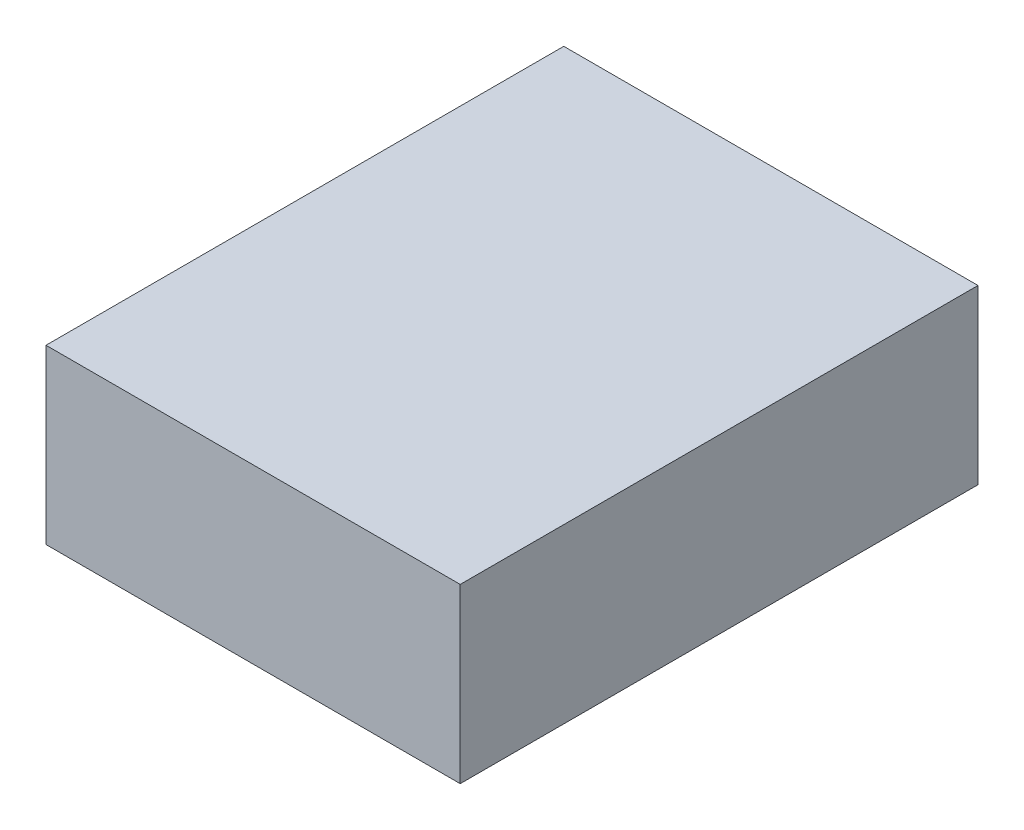
SolidWorks part; units mm, degrees
ref_plane "Front Plane" through (0, 0, 0) normal (0, 0, 1) x (1, 0, 0)
ref_plane "Top Plane" through (0, 0, 0) normal (0, 1, 0) x (1, 0, 0)
ref_plane "Right Plane" through (0, 0, 0) normal (1, 0, 0) x (0, 0, -1)
sketch "Sketch2" plane through (0, 0, 0) normal (0, 1, 0) x (1, 0, 0)
  line L1 (0, 0) -> (304.8, 0)
  line L2 (0, 0) -> (0, -381)
  line L3 (0, -381) -> (304.8, -381)
  line L4 (304.8, 0) -> (304.8, -381)
  dimension "D1" = 304.8
  dimension "D2" = 381
extrude "Boss-Extrude1" add sketch "Sketch2" along normal blind 127
